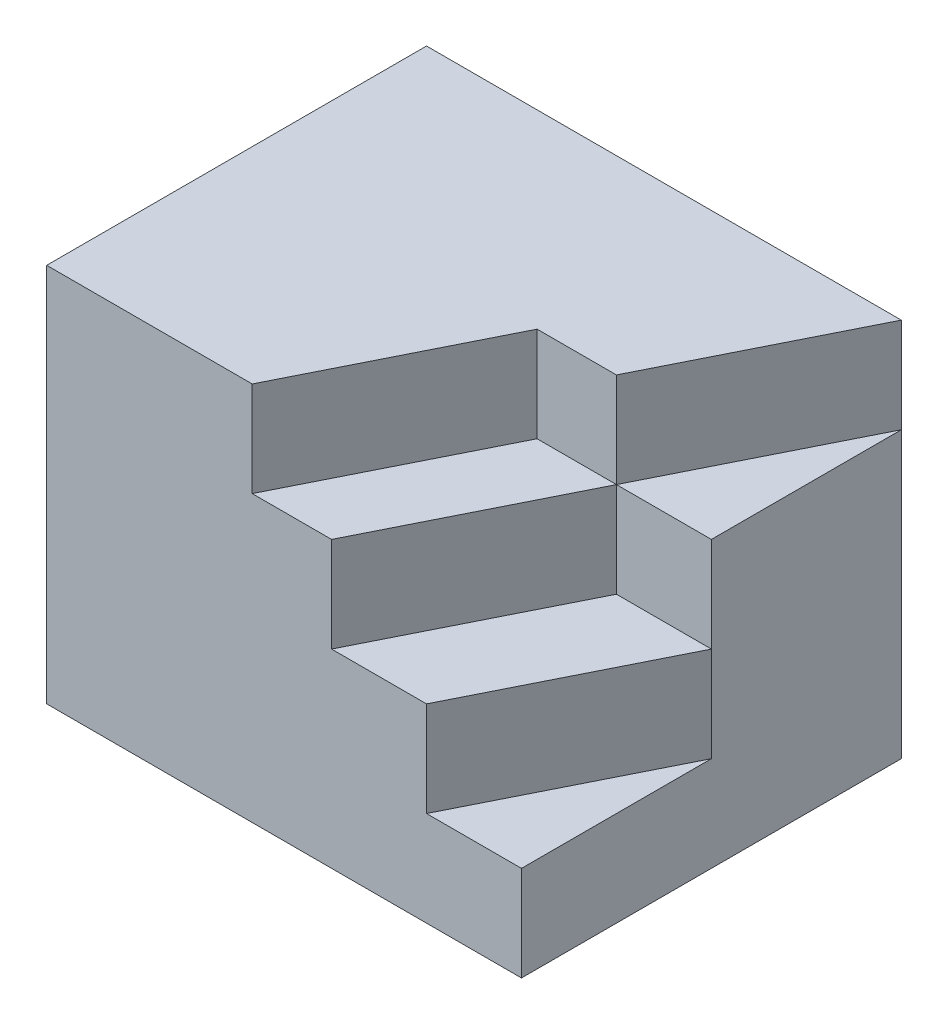
SolidWorks part; units mm, degrees
ref_plane "Front Plane" through (0, 0, 0) normal (0, 0, 1) x (1, 0, 0)
ref_plane "Top Plane" through (0, 0, 0) normal (0, 1, 0) x (1, 0, 0)
ref_plane "Right Plane" through (0, 0, 0) normal (1, 0, 0) x (0, 0, -1)
sketch "Sketch1" plane through (0, 0, 0) normal (0, 1, 0) x (1, 0, 0)
  line L1 (-25, 20) -> (25, 20)
  line L2 (-25, 20) -> (-25, -20)
  line L3 (-25, -20) -> (25, -20)
  line L4 (25, 20) -> (25, -20)
  line L5 (-25, 20) -> (25, -20) construction
  line L6 (-25, -20) -> (25, 20) construction
  point P0 (0, 0)
  dimension "D1" = 40
  dimension "D2" = 50
extrude "Boss-Extrude1" add sketch "Sketch1" along normal blind 40
sketch "Sketch2" plane through (0, 40, 0) normal (0, 1, 0) x (1, 0, 0)
  line L0 (25, 0) -> (15, -20)
  line L1 (25, -20) -> (25, 20) construction
  line L2 (-25, -20) -> (25, -20) construction
  line L3 (25, 20) -> (-25, 20) construction
  line L4 (25, 0) -> (25, -20)
  line L5 (25, -20) -> (15, -20)
  dimension "D1" = 20
  dimension "D2" = 10
extrude "Cut-Extrude1" cut sketch "Sketch2" against normal blind 30
sketch "Sketch3" plane through (0, 40, 0) normal (0, 1, 0) x (1, 0, 0)
  line L0 (15, 0) -> (5, -20)
  line L1 (-25, -20) -> (15, -20) construction
  line L2 (25, 0) -> (15, -20) construction
  line L3 (25, 0) -> (15, 0)
  line L4 (5, -20) -> (15, -20)
  line L5 (25, 0) -> (15, -20) construction
  line L6 (15, -20) -> (25, 0)
extrude "Cut-Extrude2" cut sketch "Sketch3" against normal blind 20
sketch "Sketch4" plane through (0, 40, 0) normal (0, 1, 0) x (1, 0, 0)
  line L0 (25, 20) -> (15, 0)
  line L1 (15, 0) -> (25, 0)
  line L2 (25, 0) -> (25, 20)
extrude "Cut-Extrude3" cut sketch "Sketch4" against normal blind 10
sketch "Sketch5" plane through (0, 40, 0) normal (0, 1, 0) x (1, 0, 0)
  line L0 (15, 0) -> (6.6436, 0)
  line L1 (25, 20) -> (5, -20) construction
  line L2 (6.6436, 0) -> (-3.3564, -20)
  line L3 (-25, -20) -> (5, -20) construction
  line L4 (15, 0) -> (5, -20)
  line L5 (5, -20) -> (-3.3564, -20)
extrude "Cut-Extrude4" cut sketch "Sketch5" against normal blind 10
